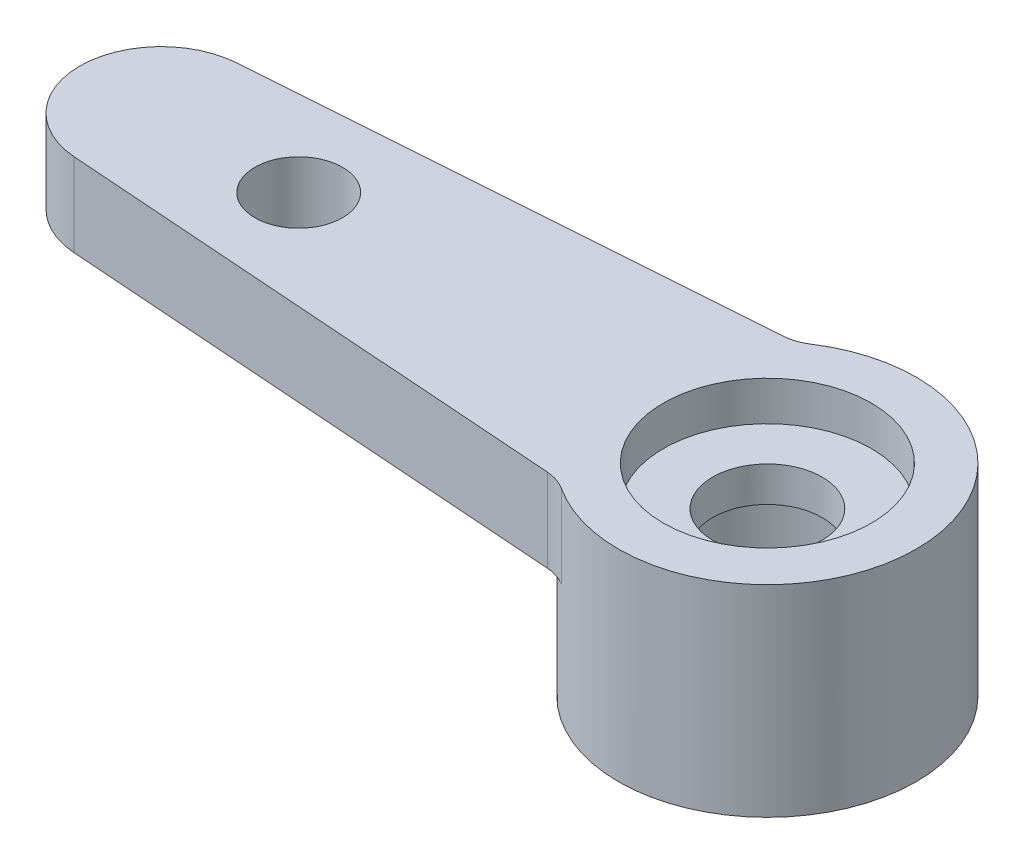
SolidWorks part; units mm, degrees
ref_plane "Front Plane" through (0, 0, 0) normal (0, 0, 1) x (1, 0, 0)
ref_plane "Top Plane" through (0, 0, 0) normal (0, 1, 0) x (1, 0, 0)
ref_plane "Right Plane" through (0, 0, 0) normal (1, 0, 0) x (0, 0, -1)
sketch "Sketch1" plane through (0, 0, 0) normal (0, 1, 0) x (1, 0, 0)
  circle A0 centre (0, 0) radius 2.325 construction
  circle A1 centre (0, 0) radius 3.4
  dimension "D1" = 4.65
  dimension "D2" = 6.8
extrude "Boss-Extrude1" add sketch "Sketch1" along normal blind 4.6
sketch "Sketch2" plane through (0, 4.6, 0) normal (0, 1, 0) x (1, 0, 0)
  line L0 (-2.0533, 2.71) -> (-2.0533, -2.71) construction
  line L1 (0, 0) -> (-15.7, 0) construction
  line L2 (-13.973, 1.8552) -> (-2.0533, 2.71)
  line L3 (-13.973, -1.8552) -> (-2.0533, -2.71)
  circle A2 centre (0, 0) radius 3.4 construction
  circle A3 centre (-13.84, 0) radius 1.86
  circle A4 centre (0, 0) radius 3.4
  point P2 (-2.0533, 0)
  point P11 (3.4, 0)
  dimension "D2" = 3.72
  dimension "D1" = 5.42
  dimension "D3" = 19.1
sketch "Sketch3" plane through (0, 4.6, 0) normal (0, 1, 0) x (1, 0, 0)
  line L0 (-13.973, -1.8552) -> (-2.0533, -2.71) construction
  line L1 (-13.973, 1.8552) -> (-2.0533, 2.71) construction
  line L2 (-13.973, -1.8552) -> (-2.0533, -2.71)
  line L3 (-13.973, 1.8552) -> (-2.0533, 2.71)
  circle A1 centre (0, 0) radius 3.4
  arc A2 (-2.0533, -2.71) -> (-2.0533, 2.71) centre (0, 0) ccw
  circle A3 centre (-13.84, 0) radius 1.86
  arc A4 (-13.973, 1.8552) -> (-13.973, -1.8552) centre (-13.84, 0) ccw
  dimension "D1" = 0
  dimension "D2" = 0
extrude "Boss-Extrude2" add sketch "Sketch3" against normal blind 1.9
sketch "Sketch4" plane through (0, 0, 0) normal (0, -1, 0) x (1, 0, 0)
  circle A0 centre (0, 0) radius 2.325 construction
  circle A1 centre (0, 0) radius 2.325
extrude "Cut-Extrude1" cut sketch "Sketch4" against normal blind 2.9
fillet "Fillet1" radius 1 2 edges at (-2.0533, 3.65, -2.71) (-2.0533, 3.65, 2.71)
sketch "Sketch5" plane through (0, 4.6, 0) normal (0, 1, 0) x (1, 0, 0)
  circle A0 centre (0, 0) radius 1.25
  dimension "D1" = 2.5
extrude "Cut-Extrude2" cut sketch "Sketch5" against normal up to next
sketch "Sketch6" plane through (0, 4.6, 0) normal (0, 1, 0) x (1, 0, 0)
  circle A0 centre (0, 0) radius 2.375
  dimension "D1" = 4.75
extrude "Cut-Extrude3" cut sketch "Sketch6" against normal blind 0.9
sketch "Sketch7" plane through (0, 4.6, 0) normal (0, 1, 0) x (1, 0, 0)
  line L0 (-15.7, 0) -> (-10.7, 0) construction
  arc A0 (-13.973, 1.8552) -> (-13.973, -1.8552) centre (-13.84, 0) ccw construction
  circle A1 centre (-10.7, 0) radius 1
  dimension "D1" = 2
  dimension "D2" = 5
extrude "Cut-Extrude4" cut sketch "Sketch7" against normal up to next
